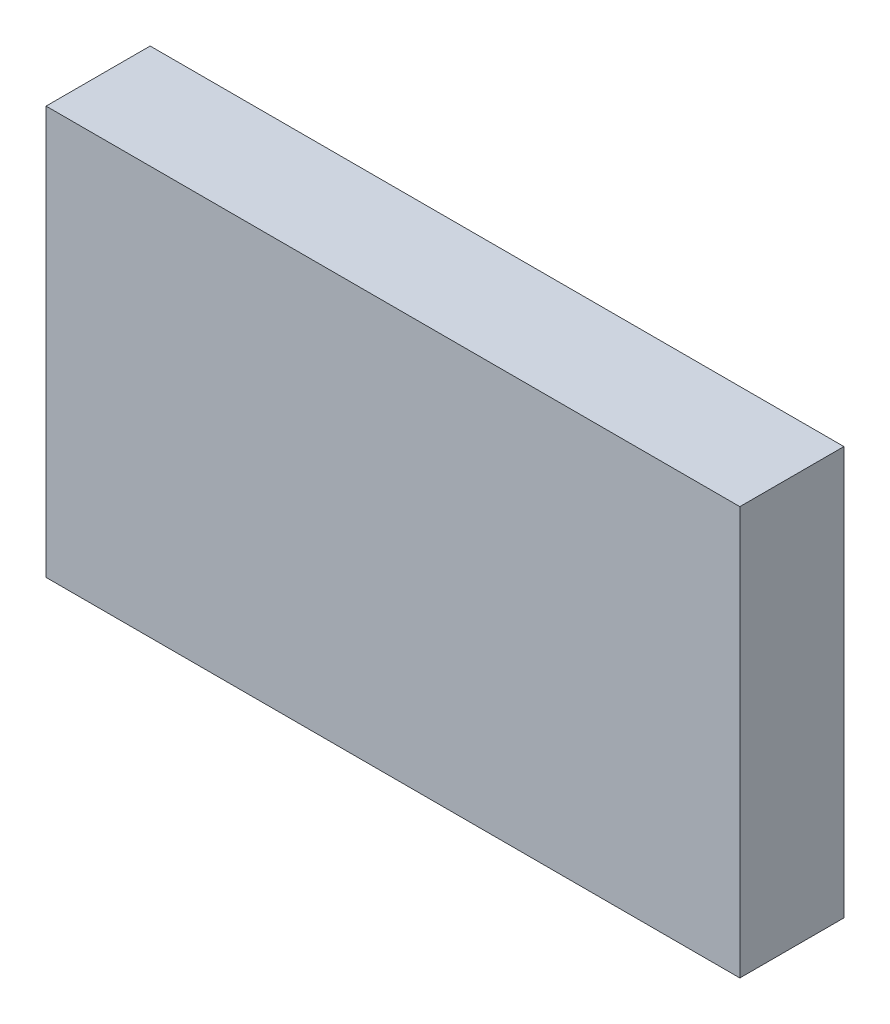
SolidWorks part; units mm, degrees
ref_plane "Plan de face" through (0, 0, 0) normal (0, 0, 1) x (1, 0, 0)
ref_plane "Plan de dessus" through (0, 0, 0) normal (0, 1, 0) x (1, 0, 0)
ref_plane "Plan de droite" through (0, 0, 0) normal (1, 0, 0) x (0, 0, -1)
sketch "Esquisse1" plane through (0, 0, 0) normal (0, 0, 1) x (1, 0, 0)
  line L1 (-10, -5.8841) -> (10, -5.8841)
  line L2 (-10, -5.8841) -> (-10, 5.8841)
  line L3 (-10, 5.8841) -> (10, 5.8841)
  line L4 (10, -5.8841) -> (10, 5.8841)
  line L5 (-10, -5.8841) -> (10, 5.8841) construction
  line L6 (-10, 5.8841) -> (10, -5.8841) construction
  point P0 (0, 0)
  dimension "D1" = 20
extrude "Boss.-Extru.1" add sketch "Esquisse1" along normal blind 3
